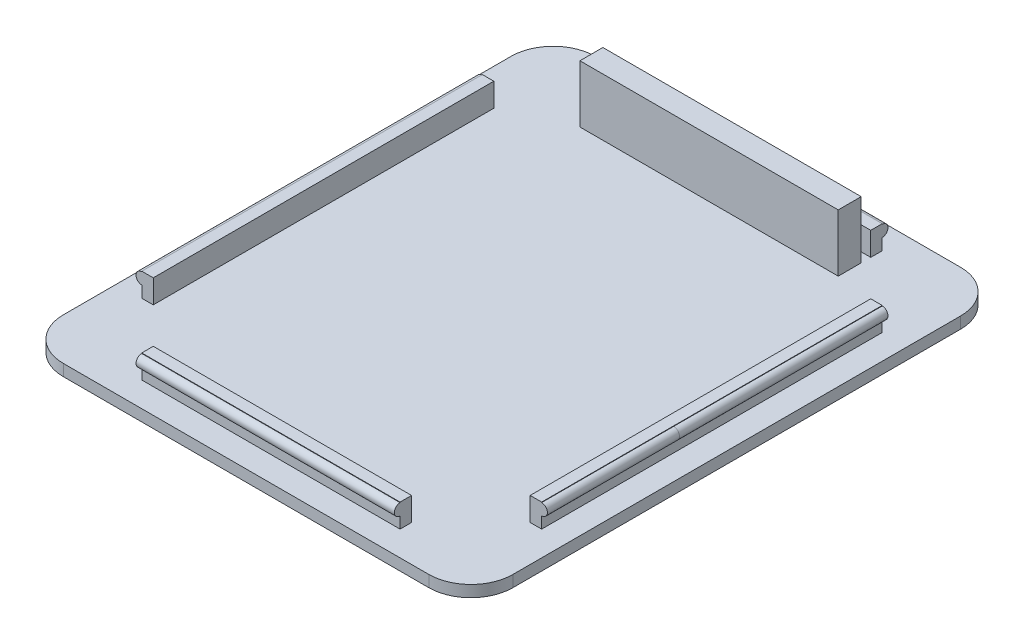
SolidWorks part; units mm, degrees
ref_plane "Front Plane" through (0, 0, 0) normal (0, 0, 1) x (1, 0, 0)
ref_plane "Top Plane" through (0, 0, 0) normal (0, 1, 0) x (1, 0, 0)
ref_plane "Right Plane" through (0, 0, 0) normal (1, 0, 0) x (0, 0, -1)
sketch "Sketch1" plane through (0, 0, 0) normal (0, 1, 0) x (1, 0, 0)
  line L0 (0.8, 25.2) -> (19.9, 25.2) construction
  line L1 (0, 0) -> (20.7, 0) construction
  line L2 (0, 0) -> (0, 25) construction
  line L3 (0, 25) -> (20.7, 25) construction
  line L4 (20.7, 0) -> (20.7, 25) construction
  line L5 (20.9, 0.8) -> (20.9, 24.2) construction
  line L6 (0.8, -0.2) -> (19.9, -0.2) construction
  line L7 (-0.2, 0.8) -> (-0.2, 24.2) construction
  line L8 (-0.2, -0.2) -> (20.9, -0.2) construction
  line L9 (20.9, -0.2) -> (20.9, 25.2) construction
  line L10 (-0.2, -0.2) -> (-0.2, 25.2) construction
  line L11 (-0.2, 25.2) -> (20.9, 25.2) construction
  line L12 (0.8, 26.4) -> (19.9, 26.4)
  line L13 (22.1, 0.8) -> (22.1, 24.2)
  line L14 (0.8, -1.4) -> (19.9, -1.4)
  line L15 (-1.4, 0.8) -> (-1.4, 24.2)
  arc A0 (19.9, -0.2) -> (20.9, 0.8) centre (19.9, 0.8) ccw construction
  arc A1 (0.8, -0.2) -> (-0.2, 0.8) centre (0.8, 0.8) cw construction
  arc A2 (-0.2, 24.2) -> (0.8, 25.2) centre (0.8, 24.2) cw construction
  arc A3 (20.9, 24.2) -> (19.9, 25.2) centre (19.9, 24.2) ccw construction
  arc A4 (22.1, 24.2) -> (19.9, 26.4) centre (19.9, 24.2) ccw
  arc A5 (19.9, -1.4) -> (22.1, 0.8) centre (19.9, 0.8) ccw
  arc A6 (0.8, -1.4) -> (-1.4, 0.8) centre (0.8, 0.8) cw
  arc A7 (-1.4, 24.2) -> (0.8, 26.4) centre (0.8, 24.2) cw
  dimension "D4" = 1
  dimension "D5" = 1.2
  dimension "D1" = 20.7
  dimension "D2" = 25
  dimension "D3" = 0.2
extrude "Boss-Extrude5" add sketch "Sketch1" along normal blind 0.6 contours L12 A4 L13 A5 L14 A6 L15 A7
sketch "Sketch13" plane through (0, 0.6, 0) normal (0, 1, 0) x (1, 0, 0)
  line L4 (19.9, 24.5) -> (0.8, 24.5)
  line L5 (0.5, 24.2) -> (0.5, 0.8)
  line L6 (0.8, 0.5) -> (19.9, 0.5)
  line L7 (20.2, 0.8) -> (20.2, 24.2)
  line L8 (-0.1, 24.2) -> (-0.1, 0.8)
  line L9 (0.8, -0.1) -> (19.9, -0.1)
  line L10 (20.8, 0.8) -> (20.8, 24.2)
  line L11 (19.9, 25.1) -> (0.8, 25.1)
  line L12 (-0.1, 24.2) -> (-0.1, 0.8)
  line L13 (0.8, -0.1) -> (19.9, -0.1)
  line L14 (20.8, 0.8) -> (20.8, 24.2)
  line L15 (19.9, 25.1) -> (0.8, 25.1)
  arc A4 (0.8, 24.5) -> (0.5, 24.2) centre (0.8, 24.2) ccw
  arc A5 (0.5, 0.8) -> (0.8, 0.5) centre (0.8, 0.8) ccw
  arc A6 (19.9, 0.5) -> (20.2, 0.8) centre (19.9, 0.8) ccw
  arc A7 (20.2, 24.2) -> (19.9, 24.5) centre (19.9, 24.2) ccw
  arc A8 (0.8, 25.1) -> (-0.1, 24.2) centre (0.8, 24.2) ccw
  arc A9 (-0.1, 0.8) -> (0.8, -0.1) centre (0.8, 0.8) ccw
  arc A10 (19.9, -0.1) -> (20.8, 0.8) centre (19.9, 0.8) ccw
  arc A11 (20.8, 24.2) -> (19.9, 25.1) centre (19.9, 24.2) ccw
  arc A12 (0.8, 25.1) -> (-0.1, 24.2) centre (0.8, 24.2) ccw
  arc A13 (-0.1, 0.8) -> (0.8, -0.1) centre (0.8, 0.8) ccw
  arc A14 (19.9, -0.1) -> (20.8, 0.8) centre (19.9, 0.8) ccw
  arc A15 (20.8, 24.2) -> (19.9, 25.1) centre (19.9, 24.2) ccw
  dimension "D1" = 1.3
  dimension "D2" = 0.6
extrude "Boss-Extrude6" add sketch "Sketch13" along normal blind 1.225
ref_plane "Plane2" through (0, 0, -10.5) normal (0, 0, -1) x (-1, 0, 0)
sketch "Sketch16" plane through (0, 1.825, 0) normal (0, 1, 0) x (1, 0, 0)
  line L4 (-0.1, 24.2) -> (-0.1, 0.8)
  line L5 (0.8, -0.1) -> (19.9, -0.1)
  line L6 (20.8, 0.8) -> (20.8, 24.2)
  line L7 (19.9, 25.1) -> (0.8, 25.1)
  line L8 (-0.1, 24.2) -> (-0.1, 0.8)
  line L9 (0.8, -0.1) -> (19.9, -0.1)
  line L10 (20.8, 0.8) -> (20.8, 24.2)
  line L11 (19.9, 25.1) -> (0.8, 25.1)
  arc A4 (0.8, 25.1) -> (-0.1, 24.2) centre (0.8, 24.2) ccw
  arc A5 (-0.1, 0.8) -> (0.8, -0.1) centre (0.8, 0.8) ccw
  arc A6 (19.9, -0.1) -> (20.8, 0.8) centre (19.9, 0.8) ccw
  arc A7 (20.8, 24.2) -> (19.9, 25.1) centre (19.9, 24.2) ccw
  arc A8 (0.8, 25.1) -> (-0.1, 24.2) centre (0.8, 24.2) ccw
  arc A9 (-0.1, 0.8) -> (0.8, -0.1) centre (0.8, 0.8) ccw
  arc A10 (19.9, -0.1) -> (20.8, 0.8) centre (19.9, 0.8) ccw
  arc A11 (20.8, 24.2) -> (19.9, 25.1) centre (19.9, 24.2) ccw
  dimension "D1" = 0
sketch "Sketch15" plane through (0, 0, -10.5) normal (0, 0, -1) x (-1, 0, 0)
  line L4 (-20.8, 1.825) -> (-20.8, 0.6) construction
  line L5 (-20.8, 1.825) -> (-20.8, 0.6) construction
  circle A0 centre (-20.8, 1.5) radius 0.3
  dimension "D1" = 0.9
  dimension "D2" = 0.6
sweep "Sweep1" add profiles "Sketch15" path "Sketch16"
sketch "Sketch17" plane through (0, 0.6, 0) normal (0, 1, 0) x (1, 0, 0)
  line L0 (0.8, 26.4) -> (19.9, 26.4) construction
  line L1 (-1.4, 26.4) -> (3.6, 26.4)
  line L2 (-1.4, 26.4) -> (-1.4, 21.4)
  line L3 (-1.4, 21.4) -> (3.6, 21.4)
  line L4 (3.6, 26.4) -> (3.6, 21.4)
  line L5 (17.1, 26.4) -> (22.1, 26.4)
  line L6 (17.1, 26.4) -> (17.1, 21.4)
  line L7 (17.1, 21.4) -> (22.1, 21.4)
  line L8 (22.1, 26.4) -> (22.1, 21.4)
  line L9 (22.1, 0.8) -> (22.1, 24.2) construction
  line L10 (-1.4, 0.8) -> (-1.4, 24.2) construction
  line L11 (17.1, 3.6) -> (22.1, 3.6)
  line L12 (17.1, 3.6) -> (17.1, -1.4)
  line L13 (17.1, -1.4) -> (22.1, -1.4)
  line L14 (22.1, 3.6) -> (22.1, -1.4)
  line L15 (3.6, 3.6) -> (-1.4, 3.6)
  line L16 (3.6, 3.6) -> (3.6, -1.4)
  line L17 (3.6, -1.4) -> (-1.4, -1.4)
  line L18 (-1.4, 3.6) -> (-1.4, -1.4)
  line L19 (0.8, -1.4) -> (19.9, -1.4) construction
  dimension "D1" = 5
extrude "Cut-Extrude1" cut sketch "Sketch17" along normal blind 10
sketch "Sketch18" plane through (0, 0.6, 0) normal (0, 1, 0) x (1, 0, 0)
  line L0 (3.6, 24.5) -> (3.6, 25.1) construction
  line L1 (3.6, 24) -> (17.1, 24)
  line L2 (3.6, 24) -> (3.6, 22.8)
  line L3 (3.6, 22.8) -> (17.1, 22.8)
  line L4 (17.1, 24) -> (17.1, 22.8)
  line L5 (17.1, 24.5) -> (17.1, 25.1) construction
  line L6 (17.1, 24.5) -> (3.6, 24.5) construction
  dimension "D1" = 1.2
  dimension "D2" = 0.5
extrude "Boss-Extrude7" add sketch "Sketch18" along normal blind 3
